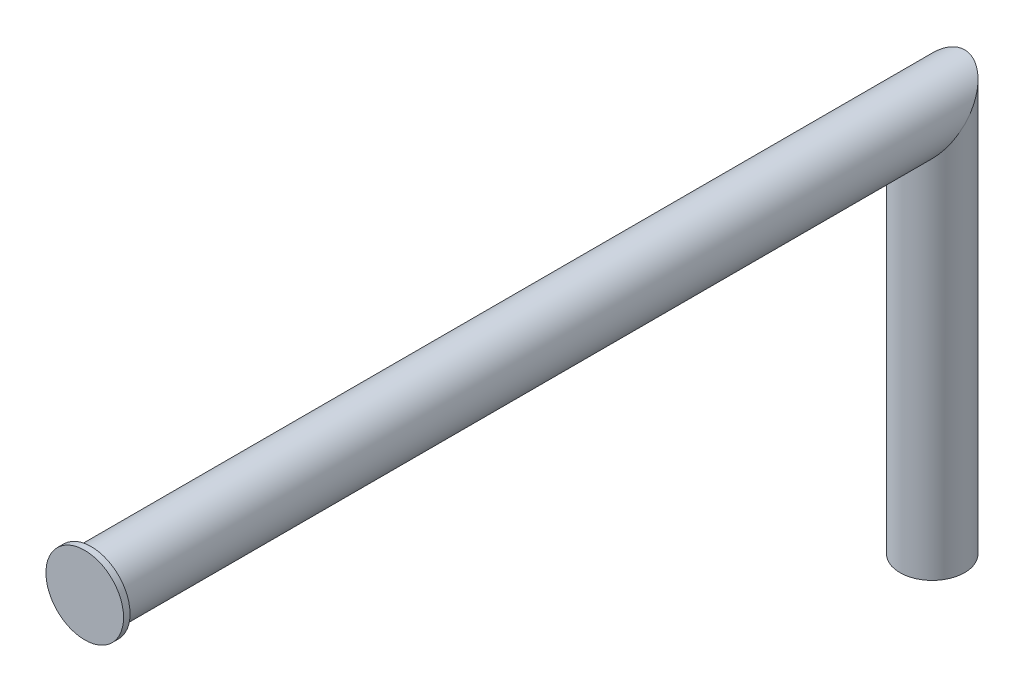
SolidWorks part; units mm, degrees
ref_plane "Front Plane" through (0, 0, 0) normal (0, 0, 1) x (1, 0, 0)
ref_plane "Top Plane" through (0, 0, 0) normal (0, 1, 0) x (1, 0, 0)
ref_plane "Right Plane" through (0, 0, 0) normal (1, 0, 0) x (0, 0, -1)
sketch "Sketch1" plane through (0, 0, 0) normal (1, 0, 0) x (0, 0, -1)
  line L0 (0, 0) -> (330.2, 0)
  line L1 (330.2, 0) -> (330.2, -152.4)
sketch "Sketch2" plane through (0, 0, 0) normal (0, 0, 1) x (1, 0, 0)
  circle A0 centre (0, 0) radius 12.7
sweep "Sweep1" add profiles "Sketch2" path "Sketch1"
sketch "Sketch3" plane through (0, 0, 0) normal (0, 0, 1) x (1, 0, 0)
  circle A0 centre (0, 0) radius 15.24
extrude "Boss-Extrude1" add sketch "Sketch3" along normal blind 2.54
ref_plane "Plane1" through (0, 10.16, 0) normal (0, 1, 0) x (1, 0, 0)
